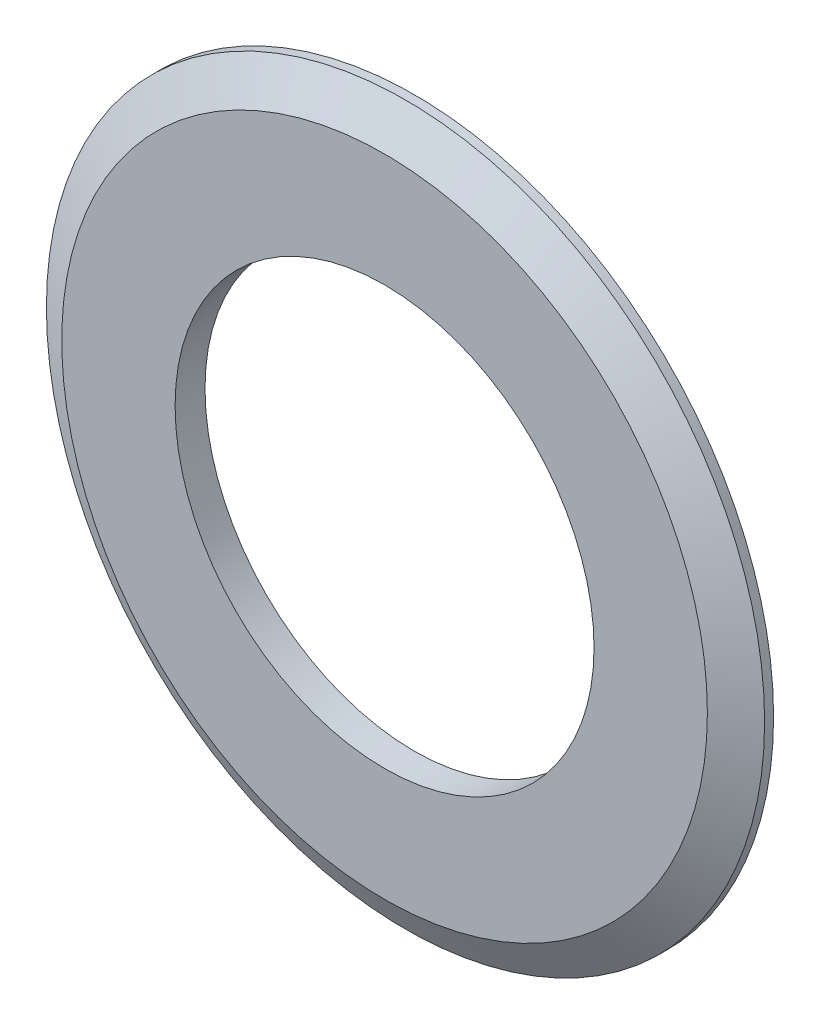
SolidWorks part; units mm, degrees
ref_plane "Front Plane" through (0, 0, 0) normal (0, 0, 1) x (1, 0, 0)
ref_plane "Top Plane" through (0, 0, 0) normal (0, 1, 0) x (1, 0, 0)
ref_plane "Right Plane" through (0, 0, 0) normal (1, 0, 0) x (0, 0, -1)
sketch "Sketch1" plane through (0, 0, 0) normal (0, 0, 1) x (1, 0, 0)
  circle A0 centre (0, 0) radius 12
  dimension "D1" = 24
extrude "Boss-Extrude1" add sketch "Sketch1" along normal blind 1
sketch "Sketch2" plane through (0, 0, 1) normal (0, 0, 1) x (1, 0, 0)
  circle A0 centre (0, 0) radius 7
  dimension "D1" = 14
extrude "Cut-Extrude1" cut sketch "Sketch2" against normal blind 1
chamfer "Chamfer1" distance 0.7 angle 60 1 edges at (12, 0, 1)
